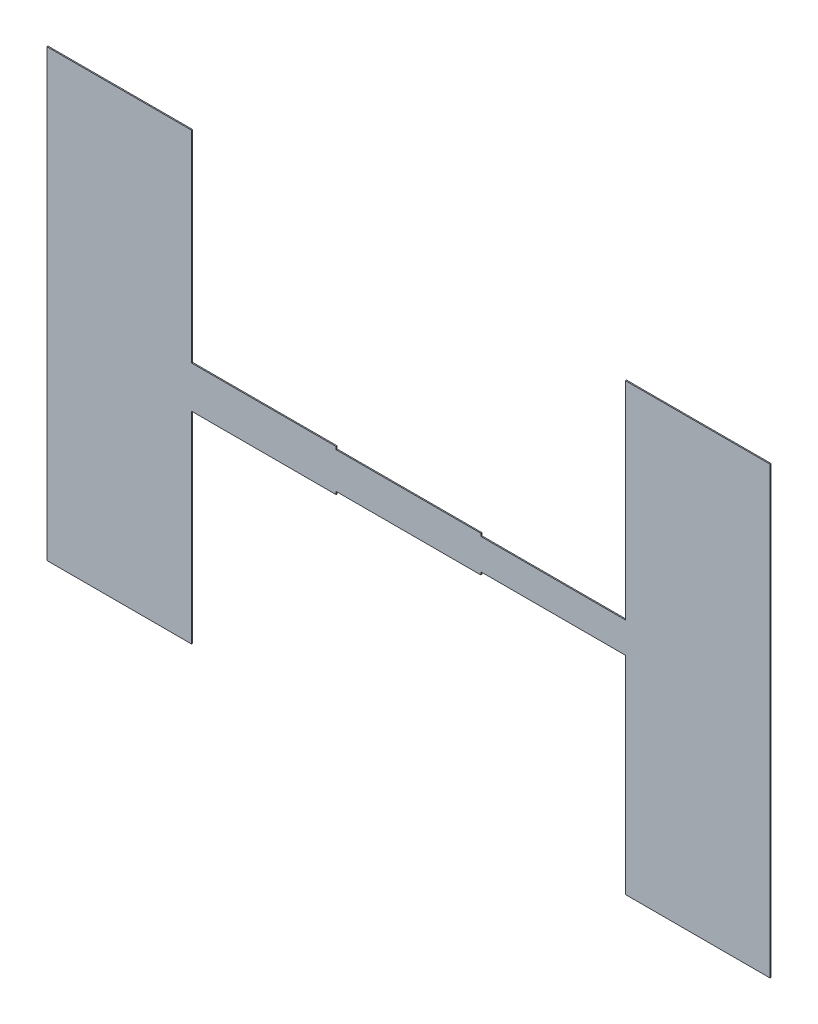
SolidWorks part; units mm, degrees
ref_plane "Front Plane" through (0, 0, 0) normal (0, 0, 1) x (1, 0, 0)
ref_plane "Top Plane" through (0, 0, 0) normal (0, 1, 0) x (1, 0, 0)
ref_plane "Right Plane" through (0, 0, 0) normal (1, 0, 0) x (0, 0, -1)
sketch "Sketch1" plane through (0, 0, 0) normal (0, 0, 1) x (1, 0, 0)
  line L0 (0, 0) -> (650, 0)
  line L1 (-650, -2000) -> (650, -2000)
  line L2 (-650, -2000) -> (-650, 2000)
  line L3 (-650, 2000) -> (650, 2000)
  line L4 (650, -2000) -> (650, -187.5)
  line L5 (-650, -2000) -> (650, 2000) construction
  line L6 (-650, 2000) -> (650, -2000) construction
  line L7 (650, 0) -> (7529.1767, 0) construction
  line L8 (650, 187.5) -> (650, 2000)
  line L9 (1950, -187.5) -> (650, -187.5)
  line L10 (1950, -187.5) -> (1950, -162.5)
  line L11 (1950, 187.5) -> (650, 187.5)
  line L13 (1950, -187.5) -> (650, 187.5) construction
  line L14 (1950, 187.5) -> (650, -187.5) construction
  line L15 (3250, -162.5) -> (1950, -162.5)
  line L16 (3250, -162.5) -> (3250, -137.5)
  line L17 (3250, 162.5) -> (1950, 162.5)
  line L19 (3250, -162.5) -> (1950, 162.5) construction
  line L20 (3250, 162.5) -> (1950, -162.5) construction
  line L21 (4550, -137.5) -> (3250, -137.5)
  line L23 (4550, 137.5) -> (3250, 137.5)
  line L25 (4550, -137.5) -> (3250, 137.5) construction
  line L26 (4550, 137.5) -> (3250, -137.5) construction
  line L27 (1950, 162.5) -> (1950, 187.5)
  line L28 (3250, 137.5) -> (3250, 162.5)
  line L29 (4550, 137.5) -> (4550, 2000)
  line L30 (5850, -2000) -> (4550, -2000)
  line L31 (5850, -2000) -> (5850, 2000)
  line L32 (5850, 2000) -> (4550, 2000)
  line L33 (4550, -2000) -> (4550, -137.5)
  line L34 (5850, -2000) -> (4550, 2000) construction
  line L35 (5850, 2000) -> (4550, -2000) construction
  point P0 (0, 0)
  point P9 (1300, 0)
  point P14 (2600, 0)
  point P19 (3900, 0)
  point P24 (5200, 0)
  dimension "D1" = 1300
  dimension "D2" = 4000
  dimension "D3" = 375
  dimension "D4" = 1300
  dimension "D5" = 1300
  dimension "D6" = 1300
  dimension "D7" = 275
  dimension "D8" = 325
  dimension "D9" = 1300
  dimension "D10" = 4000
extrude "Boss-Extrude1" add sketch "Sketch1" along normal blind 10
